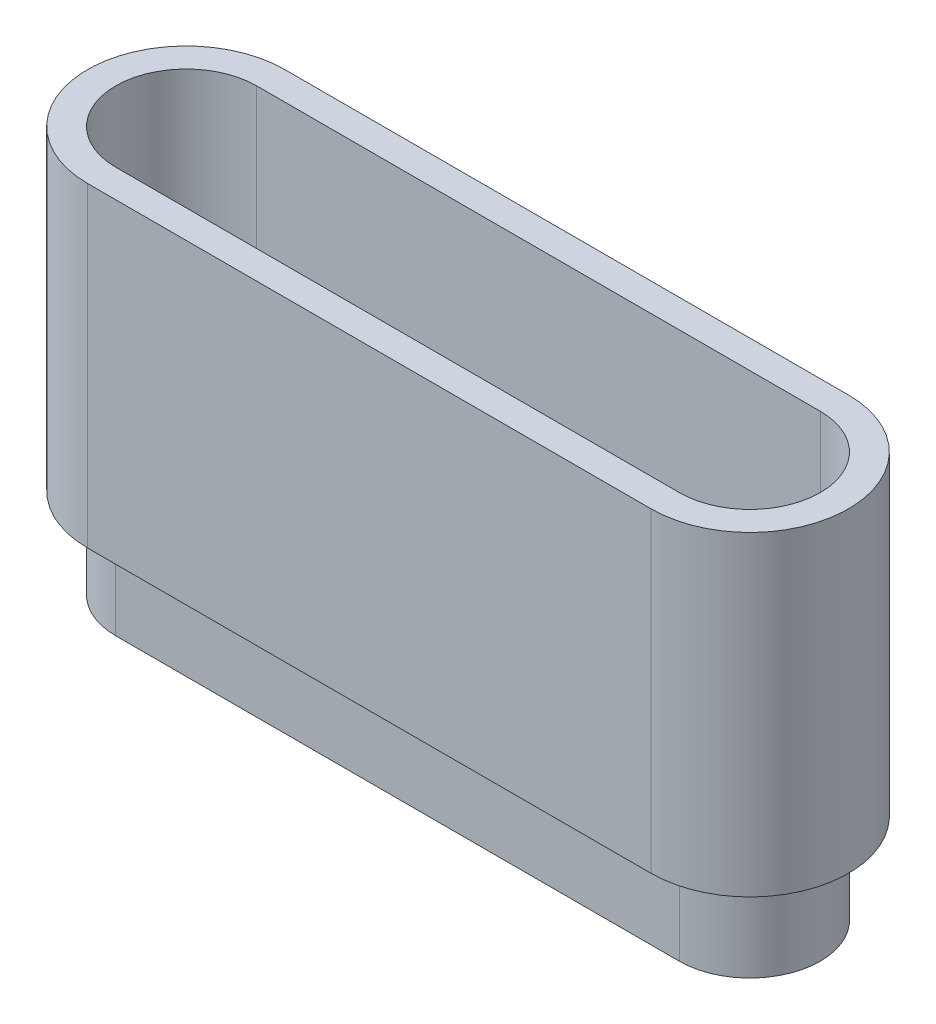
SolidWorks part; units mm, degrees
ref_plane "前视基准面" through (0, 0, 0) normal (0, 0, 1) x (1, 0, 0)
ref_plane "上视基准面" through (0, 0, 0) normal (0, 1, 0) x (1, 0, 0)
ref_plane "右视基准面" through (0, 0, 0) normal (1, 0, 0) x (0, 0, -1)
sketch "草图1" plane through (0, 0, 0) normal (0, 1, 0) x (1, 0, 0)
  line L0 (0, 0) -> (100, 0) construction
  line L1 (0, 12.5) -> (100, 12.5)
  line L2 (0, -12.5) -> (100, -12.5)
  arc A0 (0, 12.5) -> (0, -12.5) centre (0, 0) ccw
  arc A1 (100, -12.5) -> (100, 12.5) centre (100, 0) ccw
  point P3 (50, 0)
  dimension "D1" = 100
  dimension "D2" = 25
extrude "凸台-拉伸2" add sketch "草图1" along normal blind 16 contours L1 A1 L2 A0
sketch "草图5" plane through (0, 16, 0) normal (0, 1, 0) x (1, 0, 0)
  line L2 (0, -12.5) -> (100, -12.5)
  line L3 (100, 12.5) -> (0, 12.5)
  line L4 (0, -12.5) -> (100, -12.5)
  line L5 (100, 12.5) -> (0, 12.5)
  arc A2 (0, 12.5) -> (0, -12.5) centre (0, 0) ccw
  arc A3 (100, -12.5) -> (100, 12.5) centre (100, 0) ccw
  arc A4 (0, 12.5) -> (0, -12.5) centre (0, 0) ccw
  arc A5 (100, -12.5) -> (100, 12.5) centre (100, 0) ccw
  dimension "D1" = 0
extrude "拉伸-薄壁1" add sketch "草图5" along normal blind 56 separate body thin
